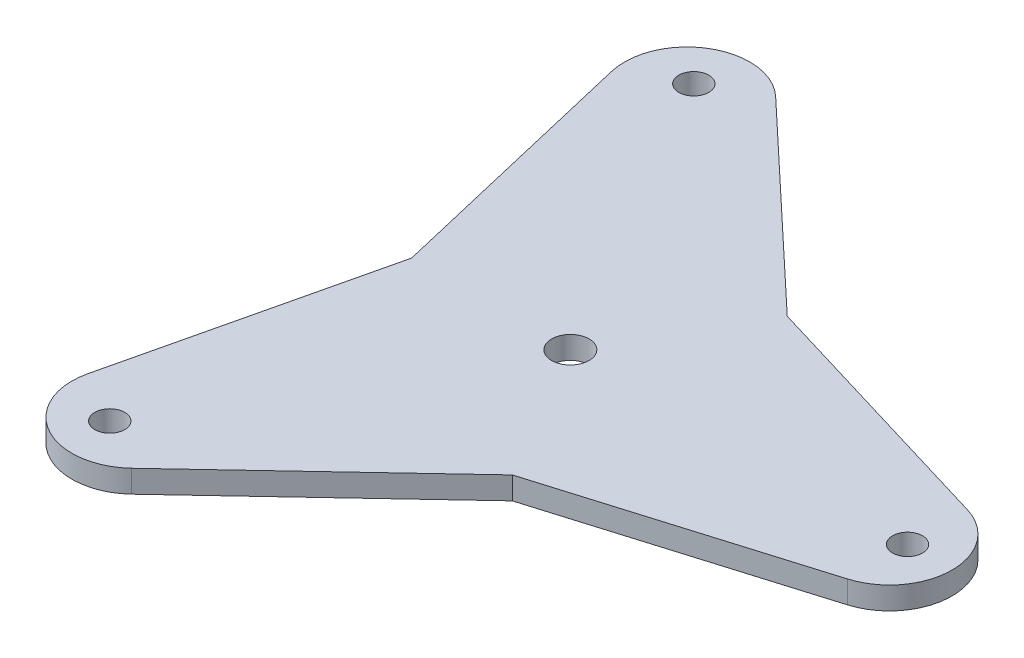
SolidWorks part; units mm, degrees
material "1060 Alloy"
ref_plane "Front" through (0, 0, 0) normal (0, 0, 1) x (1, 0, 0)
ref_plane "Top" through (0, 0, 0) normal (0, 1, 0) x (1, 0, 0)
ref_plane "Right" through (0, 0, 0) normal (1, 0, 0) x (0, 0, -1)
sketch "Sketch2" plane through (0, 0, 0) normal (0, 1, 0) x (1, 0, 0)
  line L0 (-22.5017, 38.9741) -> (0, 0) construction
  line L1 (0, 0) -> (45.0034, 0) construction
  line L2 (0, 0) -> (-22.5017, -38.9741) construction
  line L3 (10.5945, -18.3501) -> (45, -8)
  line L5 (10.5945, 18.3501) -> (45, 8)
  line L6 (-21.1889, 0) -> (-29.4282, -34.9711)
  line L7 (10.5945, -18.3501) -> (-15.5718, -42.9711)
  line L8 (-21.1889, 0) -> (-29.4282, 34.9711)
  line L9 (10.5945, 18.3501) -> (-15.5718, 42.9711)
  circle A0 centre (0, 0) radius 2.5
  circle A1 centre (-22.5017, 38.9741) radius 2
  circle A2 centre (45.0034, 0) radius 2
  circle A3 centre (-22.5017, -38.9741) radius 2
  arc A4 (45, 8) -> (45, -8) centre (42.5934, 0) cw
  arc A5 (-15.5718, -42.9711) -> (-29.4282, -34.9711) centre (-21.2967, -36.8869) cw
  arc A6 (-29.4282, 34.9711) -> (-15.5718, 42.9711) centre (-21.2967, 36.8869) cw
  point P12 (0, 0)
  point P29 (0, 0)
  point P32 (0, 0)
  point P33 (0, 0)
  point P38 (0, 0)
  dimension "D3" = 3
  dimension "D4" = 4
  dimension "D7" = 5
  dimension "D2" = 8.3541
  dimension "D5" = 22.5017
  dimension "D8" = 38.9741
  dimension "D1" = 3
  dimension "D6" = 3
extrude "Boss-Extrude2" add sketch "Sketch2" along normal blind 3
